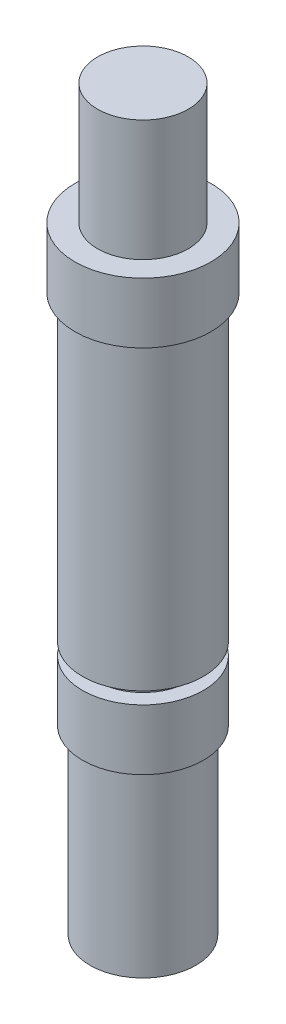
SolidWorks part; units mm, degrees
ref_plane "前视基准面" through (0, 0, 0) normal (0, 0, 1) x (1, 0, 0)
ref_plane "上视基准面" through (0, 0, 0) normal (0, 1, 0) x (1, 0, 0)
ref_plane "右视基准面" through (0, 0, 0) normal (1, 0, 0) x (0, 0, -1)
sketch "草图1" plane through (0, 0, 0) normal (0, 1, 0) x (1, 0, 0)
  circle A0 centre (0, 0) radius 17.5
  dimension "D1" = 35
extrude "凸台-拉伸1" add sketch "草图1" along normal blind 60 contours A0
sketch "草图2" plane through (0, 60, 0) normal (0, 1, 0) x (1, 0, 0)
  circle A0 centre (0, 0) radius 20
extrude "凸台-拉伸2" add sketch "草图2" along normal blind 20
sketch "草图3" plane through (0, 80, 0) normal (0, 1, 0) x (1, 0, 0)
  circle A0 centre (0, 0) radius 15
extrude "凸台-拉伸3" add sketch "草图3" along normal blind 4
sketch "草图4" plane through (0, 84, 0) normal (0, 1, 0) x (1, 0, 0)
  circle A0 centre (0, 0) radius 20
extrude "凸台-拉伸4" add sketch "草图4" along normal blind 100
sketch "草图5" plane through (0, 184, 0) normal (0, 1, 0) x (1, 0, 0)
  circle A0 centre (0, 0) radius 22.5
extrude "凸台-拉伸5" add sketch "草图5" along normal blind 20
sketch "草图6" plane through (0, 204, 0) normal (0, 1, 0) x (1, 0, 0)
  circle A0 centre (0, 0) radius 15
extrude "凸台-拉伸6" add sketch "草图6" along normal blind 40
